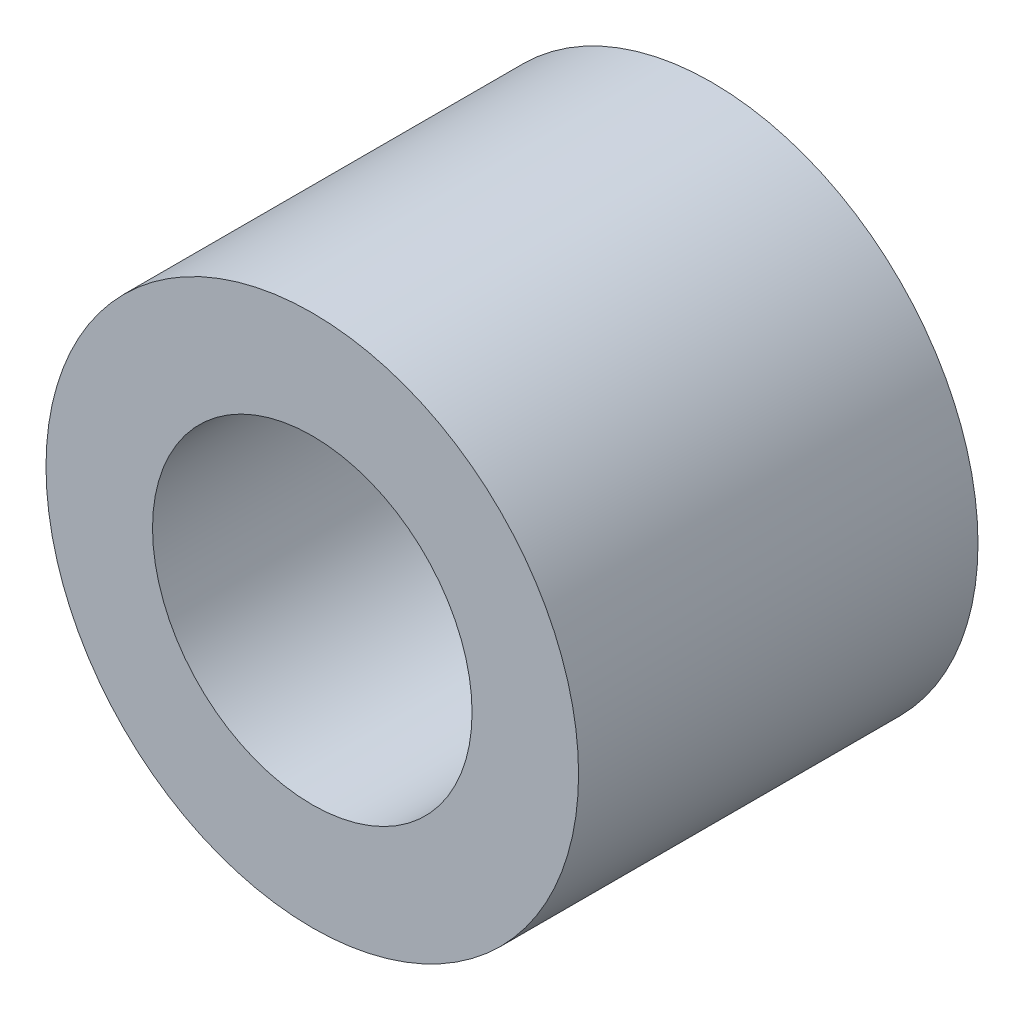
SolidWorks part; units mm, degrees
ref_plane "Alzado" through (0, 0, 0) normal (0, 0, 1) x (1, 0, 0)
ref_plane "Planta" through (0, 0, 0) normal (0, 1, 0) x (1, 0, 0)
ref_plane "Vista lateral" through (0, 0, 0) normal (1, 0, 0) x (0, 0, -1)
sketch "Croquis1" plane through (0, 0, 0) normal (0, 0, 1) x (1, 0, 0)
  circle A0 centre (0, 0) radius 2
  circle A1 centre (0, 0) radius 1.2
  dimension "D1" = 4
  dimension "D2" = 2.4
extrude "Saliente-Extruir1" add sketch "Croquis1" along normal blind 3
